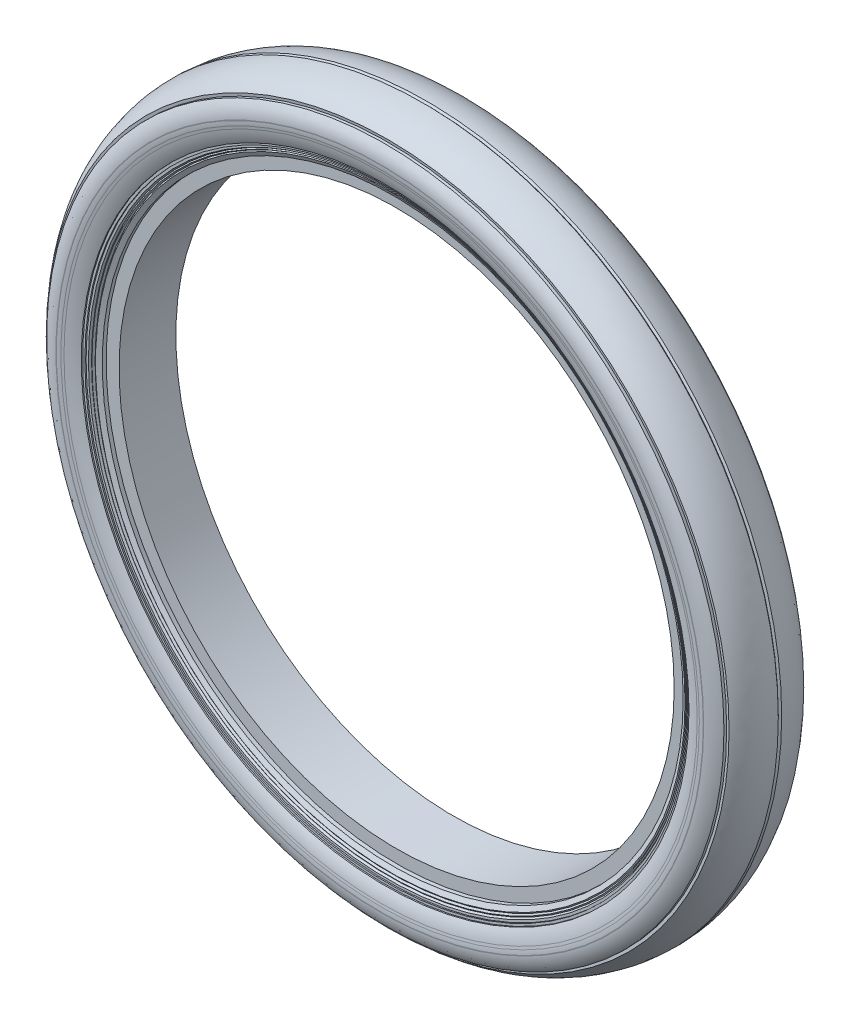
SolidWorks part; units mm, degrees
ref_plane "Спереди" through (0, 0, 0) normal (0, 0, 1) x (1, 0, 0)
ref_plane "Сверху" through (0, 0, 0) normal (0, 1, 0) x (1, 0, 0)
ref_plane "Справа" through (0, 0, 0) normal (1, 0, 0) x (0, 0, -1)
sketch "Эскиз2" plane through (0, 0, 0) normal (1, 0, 0) x (0, 0, -1)
  line L0 (0, 0) -> (0, 275) construction
  line L1 (0, 273.6698) -> (-1.3132, 274.983)
  line L2 (22, 215) -> (-22, 215)
  line L3 (-22, 215) -> (-22, 225)
  line L4 (-22, 225) -> (-25, 225)
  line L5 (22, 215) -> (22, 225)
  line L6 (22, 225) -> (25, 225)
  line L7 (-35, 250.8827) -> (-35, 250.5373)
  line L8 (0, 273.6698) -> (1.3132, 274.983)
  line L9 (-34.7281, 247.2506) -> (-34.3956, 245.2547)
  line L10 (-26.8891, 228.3258) -> (-25, 225)
  line L11 (-22, 0) -> (25, 0) construction
  line L12 (34.7281, 247.2506) -> (34.3956, 245.2547)
  line L13 (35, 250.8827) -> (35, 250.5373)
  line L14 (-30.8891, 235.3679) -> (-29.8891, 235.3679)
  line L15 (-29.8891, 235.3679) -> (-29.8891, 233.6074)
  line L16 (-29.8891, 233.6074) -> (-28.8891, 233.6074)
  line L17 (-28.8891, 233.6074) -> (-28.8891, 231.8468)
  line L18 (26.8891, 228.3258) -> (26.3769, 229.1847)
  line L19 (-27.3769, 230.9452) -> (-28.8891, 231.8468)
  line L20 (-27.8891, 230.0863) -> (-27.3769, 230.9452)
  line L21 (-26.3769, 229.1847) -> (-27.8891, 230.0863)
  line L22 (-26.8891, 228.3258) -> (-26.3769, 229.1847)
  line L23 (26.3769, 229.1847) -> (27.8891, 230.0863)
  line L24 (27.8891, 230.0863) -> (27.3769, 230.9452)
  line L25 (27.3769, 230.9452) -> (28.8891, 231.8468)
  line L26 (28.8891, 233.6074) -> (28.8891, 231.8468)
  line L27 (29.8891, 233.6074) -> (28.8891, 233.6074)
  line L28 (29.8891, 235.3679) -> (29.8891, 233.6074)
  line L29 (30.8891, 235.3679) -> (29.8891, 235.3679)
  line L30 (26.8891, 228.3258) -> (25, 225)
  line L31 (28.6665, 262.3503) -> (30.7902, 262.3503)
  line L32 (-28.6665, 262.3503) -> (-30.7902, 262.3503)
  line L33 (-28.6665, 262.3503) -> (-28.9276, 264.4591)
  line L34 (28.6665, 262.3503) -> (28.9276, 264.4591)
  arc A0 (-30.8891, 235.3679) -> (-34.3956, 245.2547) centre (-4.8035, 250.1848) cw
  arc A1 (-34.7281, 247.2506) -> (-35, 250.5373) centre (-15, 250.5373) cw
  arc A2 (30.8891, 235.3679) -> (34.3956, 245.2547) centre (4.8035, 250.1848) ccw
  arc A3 (34.7281, 247.2506) -> (35, 250.5373) centre (15, 250.5373) ccw
  ellipse E0 centre (0, 250.8827) end of major axis (-35, 250.8827) minor radius 24.1173 (35, 250.8827) -> (30.7902, 262.3503) ccw
  ellipse E1 centre (0, 250.8827) end of major axis (-35, 250.8827) minor radius 24.1173 (-1.3132, 274.983) -> (-28.9276, 264.4591) ccw
  ellipse E2 centre (0, 250.8827) end of major axis (-35, 250.8827) minor radius 24.1173 (-30.7902, 262.3503) -> (-35, 250.8827) ccw
  ellipse E3 centre (0, 250.8827) end of major axis (-35, 250.8827) minor radius 24.1173 (28.9276, 264.4591) -> (1.3132, 274.983) ccw
  point P3 (0, 225)
  point P4 (0, 240)
  point P25 (-33.5201, 240)
  point P28 (-35, 248.8827)
  point P36 (0, 215)
  dimension "D3" = 35
  dimension "D4" = 22
  dimension "D9" = 30
  dimension "D10" = 20
  dimension "D1" = 275
  dimension "D2" = 50
  dimension "D5" = 10
  dimension "D6" = 3
  dimension "D7" = 35
  dimension "D8" = 2
  dimension "D11" = 1
  dimension "D12" = 1
revolve "Повернуть1" add sketch "Эскиз2" angle 360 about L11
